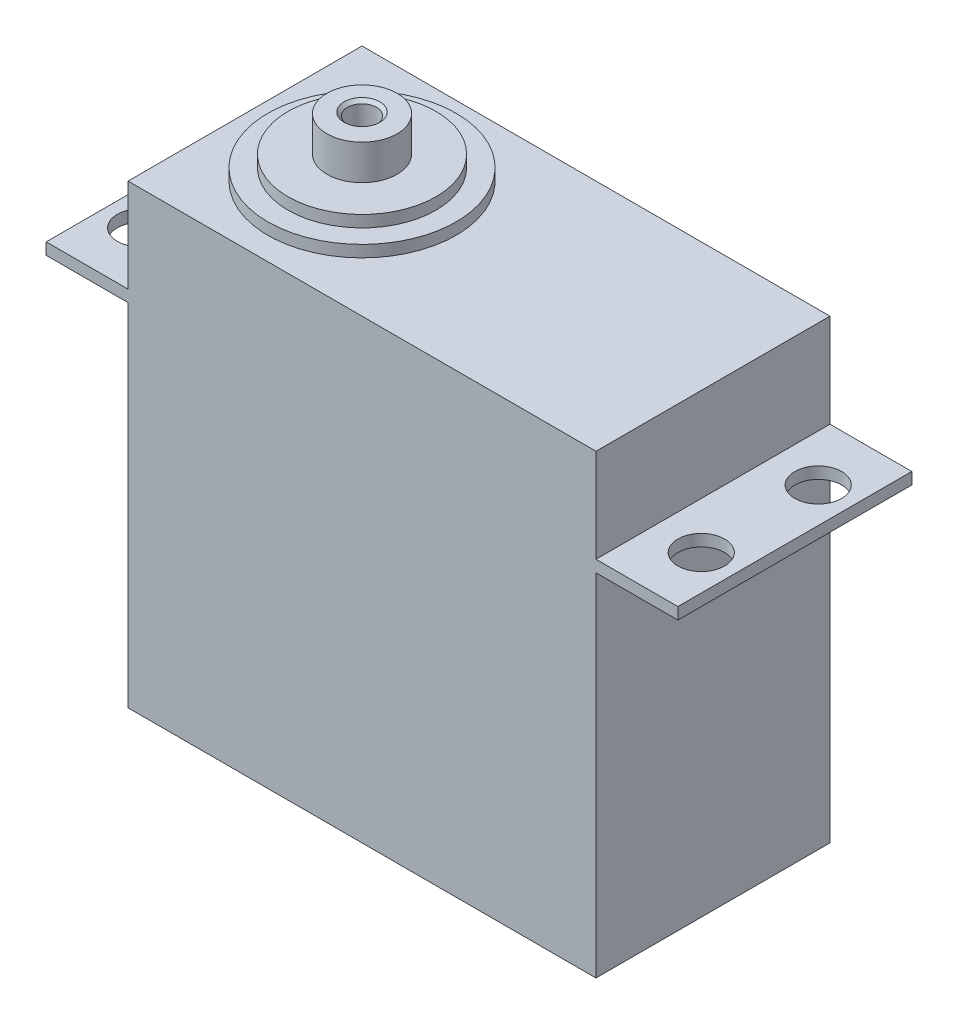
SolidWorks part; units mm, degrees
ref_plane "前视基准面" through (0, 0, 0) normal (0, 0, 1) x (1, 0, 0)
ref_plane "上视基准面" through (0, 0, 0) normal (0, 1, 0) x (1, 0, 0)
ref_plane "右视基准面" through (0, 0, 0) normal (1, 0, 0) x (0, 0, -1)
other "Configuration Table"
sketch "草图1" plane through (0, 0, 0) normal (0, 0, 1) x (1, 0, 0)
  line L1 (-20, 19.5) -> (20, 19.5)
  line L2 (-20, 19.5) -> (-20, -19.5)
  line L3 (-20, -19.5) -> (20, -19.5)
  line L4 (20, 19.5) -> (20, -19.5)
  line L5 (-20, 19.5) -> (20, -19.5) construction
  line L6 (-20, -19.5) -> (20, 19.5) construction
  point P0 (0, 0)
  dimension "D1" = 40
  dimension "D2" = 39
extrude "凸台-拉伸1" add sketch "草图1" along normal blind 20
ref_plane "基准面1" through (-20, 0, 0) normal (-1, 0, 0) x (0, 0, 1)
sketch "草图2" plane through (-20, 0, 0) normal (-1, 0, 0) x (0, 0, 1)
  line L0 (0, -19.5) -> (0, 11.5)
  line L1 (0, 19.5) -> (0, -19.5) construction
  line L2 (20, 19.5) -> (20, -19.5) construction
  line L3 (0, 11.5) -> (20, 11.5)
  line L4 (0, 11.5) -> (0, 10.5)
  line L5 (0, 10.5) -> (20, 10.5)
  line L6 (20, 11.5) -> (20, 10.5)
  dimension "D1" = 31
  dimension "D2" = 1
extrude "凸台-拉伸2" add sketch "草图2" along normal blind 7 contours L6 L3 L0 L5
ref_plane "基准面2" through (20, 0, 0) normal (1, 0, 0) x (0, 0, -1)
sketch "草图3" plane through (20, 0, 0) normal (1, 0, 0) x (0, 0, -1)
  line L0 (-20, 10.5) -> (-20, 11.5)
  line L1 (-20, -19.5) -> (-20, 19.5) construction
  line L2 (0, -19.5) -> (0, 19.5) construction
  line L3 (-20, 11.5) -> (0, 11.5)
  line L4 (-20, 11.5) -> (-20, 10.5)
  line L5 (-20, 10.5) -> (0, 10.5)
  line L6 (0, 11.5) -> (0, 10.5)
  dimension "D2" = 1
extrude "凸台-拉伸3" add sketch "草图3" along normal blind 7 contours L6 L3 L0 L5
ref_plane "基准面3" through (0, 11.5, 0) normal (0, 1, 0) x (1, 0, 0)
sketch "草图5" plane through (0, 11.5, 0) normal (0, 1, 0) x (1, 0, 0)
  line L0 (-20, 0) -> (-24, 0)
  line L1 (-27, 0) -> (-20, 0) construction
  line L3 (-27, -10) -> (-20, -10) construction
  line L4 (-27, 0) -> (-27, -20) construction
  circle A0 centre (-24, -5.0738) radius 2
  circle A1 centre (-24, -14.9262) radius 2
  dimension "D2" = 4
  dimension "D1" = 4
extrude "切除-拉伸1" cut sketch "草图5" against normal through all contours A0 | A1
ref_plane "基准面4" through (0, 11.5, 0) normal (0, 1, 0) x (1, 0, 0)
sketch "草图6" plane through (0, 11.5, 0) normal (0, 1, 0) x (1, 0, 0)
  line L3 (27, -10) -> (20, -10) construction
  line L4 (27, -20) -> (27, 0) construction
  circle A0 centre (24, -5) radius 2
  circle A1 centre (24, -15) radius 2
  dimension "D3" = 4
extrude "切除-拉伸2" cut sketch "草图6" against normal through all
ref_plane "基准面5" through (0, 19.5, 0) normal (0, 1, 0) x (1, 0, 0)
sketch "草图7" plane through (0, 19.5, 0) normal (0, 1, 0) x (1, 0, 0)
  line L0 (-20, -10) -> (-10, -10)
  line L1 (-20, -20) -> (-20, 0) construction
  circle A0 centre (-10, -10) radius 8.0451
  dimension "D1" = 10
extrude "凸台-拉伸4" add sketch "草图7" along normal blind 1 contours A0
sketch "草图8" plane through (0, 20.5, 0) normal (0, 1, 0) x (1, 0, 0)
  circle A0 centre (-10, -10) radius 6.3237
extrude "凸台-拉伸5" add sketch "草图8" along normal blind 1
sketch "草图9" plane through (0, 21.5, 0) normal (0, 1, 0) x (1, 0, 0)
  circle A0 centre (-10, -10) radius 3
  dimension "D1" = 6
extrude "凸台-拉伸6" add sketch "草图9" along normal blind 3
hole_wizard "M3 螺纹孔1" positions "3D草图1" profile "草图10" tap size "M3" standard "GB"
sketch3d "3D草图1"
  point P0 (-10.1095, 24.5, 9.891)
cosmetic thread "孔螺蚊线1" parameters "D1"=12, "D2"=3
sketch "草图10" plane through (-10.1095, 24.5, 9.891) normal (1, 0, 0) x (0, 0, 1)
  line L0 (0, 0) -> (0, 15.2511)
  line L1 (0, 15.2511) -> (1.25, 14.5)
  line L2 (1.25, 14.5) -> (1.25, 0.275)
  line L3 (1.25, 0.275) -> (1.525, 0)
  line L5 (1.525, 0) -> (0, 0)
  line L6 (-1.25, 0.275) -> (-1.525, 0) construction
  line L10 (0, 15.2511) -> (-1.25, 14.5) construction
  line L11 (0, -6.35) -> (0, 107.95) construction
  dimension "螺纹孔钻头直径" = 2.5
  dimension "螺纹孔钻头深度" = 14.5
  dimension "近端锥形沉头孔直径" = 3.05
  dimension "近端锥形沉头孔角度" = 90
  dimension "导头角度" = 118
equation "\"0.5.mm\"=1"
